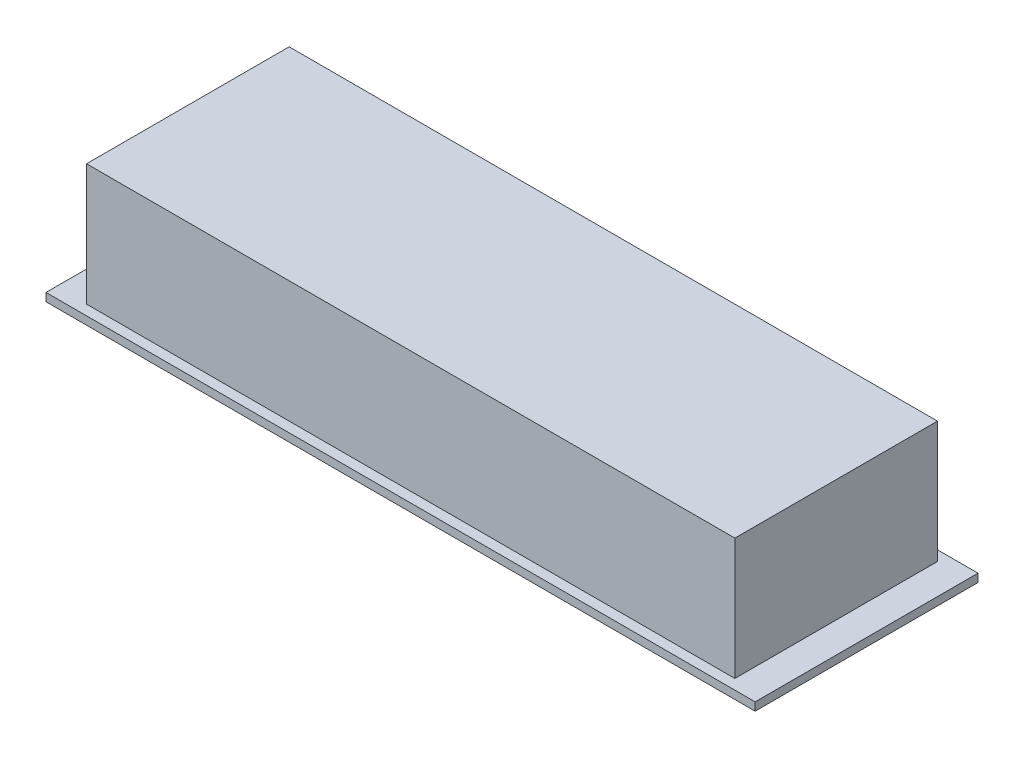
SolidWorks part; units mm, degrees
ref_plane "Front" through (0, 0, 0) normal (0, 0, 1) x (1, 0, 0)
ref_plane "Top" through (0, 0, 0) normal (0, 1, 0) x (1, 0, 0)
ref_plane "Right" through (0, 0, 0) normal (1, 0, 0) x (0, 0, -1)
sketch "Sketch1" plane through (0, 0, 0) normal (0, 1, 0) x (1, 0, 0)
  line L1 (-101.6, 31.75) -> (101.6, 31.75)
  line L2 (-101.6, 31.75) -> (-101.6, -31.75)
  line L3 (-101.6, -31.75) -> (101.6, -31.75)
  line L4 (101.6, 31.75) -> (101.6, -31.75)
  line L5 (-101.6, 31.75) -> (101.6, -31.75) construction
  line L6 (-101.6, -31.75) -> (101.6, 31.75) construction
  point P0 (0, 0)
  dimension "D1" = 203.2
  dimension "D2" = 63.5
extrude "Boss-Extrude1" add sketch "Sketch1" along normal blind 38.1
sketch "Sketch2" plane through (0, 0, 0) normal (0, -1, 0) x (1, 0, 0)
  line L0 (101.6, 31.75) -> (101.6, -31.75) construction
  line L1 (-111.125, 34.925) -> (111.125, 34.925)
  line L2 (-111.125, 34.925) -> (-111.125, -34.925)
  line L3 (-111.125, -34.925) -> (111.125, -34.925)
  line L4 (111.125, 34.925) -> (111.125, -34.925)
  line L5 (-111.125, 34.925) -> (111.125, -34.925) construction
  line L6 (-111.125, -34.925) -> (111.125, 34.925) construction
  line L7 (-101.6, 31.75) -> (101.6, 31.75) construction
  point P0 (0, 0)
  dimension "D1" = 9.525
  dimension "D2" = 3.175
extrude "Boss-Extrude2" add sketch "Sketch2" along normal blind 2.54
